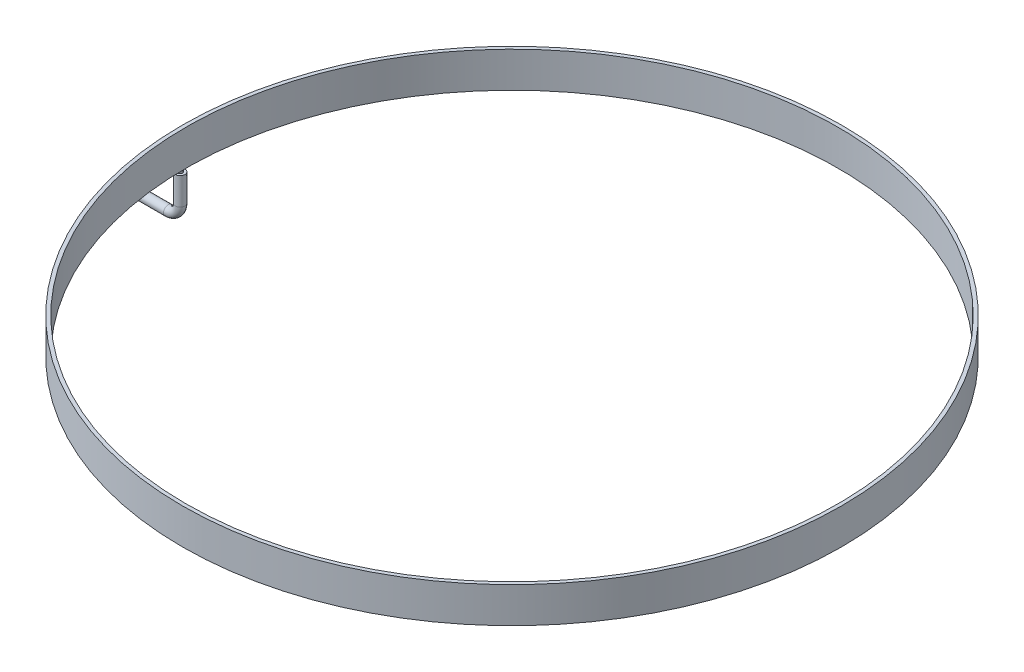
SolidWorks part; units mm, degrees
ref_plane "Front Plane" through (0, 0, 0) normal (0, 0, 1) x (1, 0, 0)
ref_plane "Top Plane" through (0, 0, 0) normal (0, 1, 0) x (1, 0, 0)
ref_plane "Right Plane" through (0, 0, 0) normal (1, 0, 0) x (0, 0, -1)
sketch "Sketch1" plane through (0, 0, 0) normal (0, 1, 0) x (1, 0, 0)
  circle A0 centre (0, 0) radius 27.8
  circle A1 centre (0, 0) radius 27.5
  dimension "D1" = 55.6
  dimension "D2" = 0.3
extrude "Boss-Extrude1" add sketch "Sketch1" along normal mid plane 3
sketch "Sketch2" plane through (0, 0, 0) normal (0, 0, 1) x (1, 0, 0)
  line L0 (-27.98, -1) -> (-27.98, -2)
  line L1 (-27.8, 1.5) -> (-27.8, -1.5) construction
  line L2 (0, 0) -> (50000, 0) construction
  dimension "D1" = 1
  dimension "D2" = 0.18
  dimension "D3" = 1
sweep "Sweep1" add path "Sketch2" circular profile diameter 0.4 parameters "D3"=0.4
sketch "Sketch33" plane through (0, -2, 0) normal (0, -1, 0) x (1, 0, 0)
  circle A0 centre (-27.98, 0) radius 0.4
  dimension "D1" = 0.8
extrude "Boss-Extrude2" add sketch "Sketch33" along normal blind 1
sketch "Sketch34" plane through (0, 0, 0) normal (0, 0, 1) x (1, 0, 0)
  line L0 (-27.98, -2) -> (-27.98, -4.3)
  line L1 (-27.58, -2) -> (-28.38, -2) construction
  line L2 (-28.98, -5.3) -> (-32.98, -5.3)
  arc A0 (-27.98, -4.3) -> (-28.98, -5.3) centre (-28.98, -4.3) cw
  point P7 (-27.98, -5.3)
  dimension "D3" = 1
  dimension "D1" = 3.3
  dimension "D2" = 5
sweep "Sweep2" add path "Sketch34" circular profile diameter 0.8 parameters "D3"=0.8
